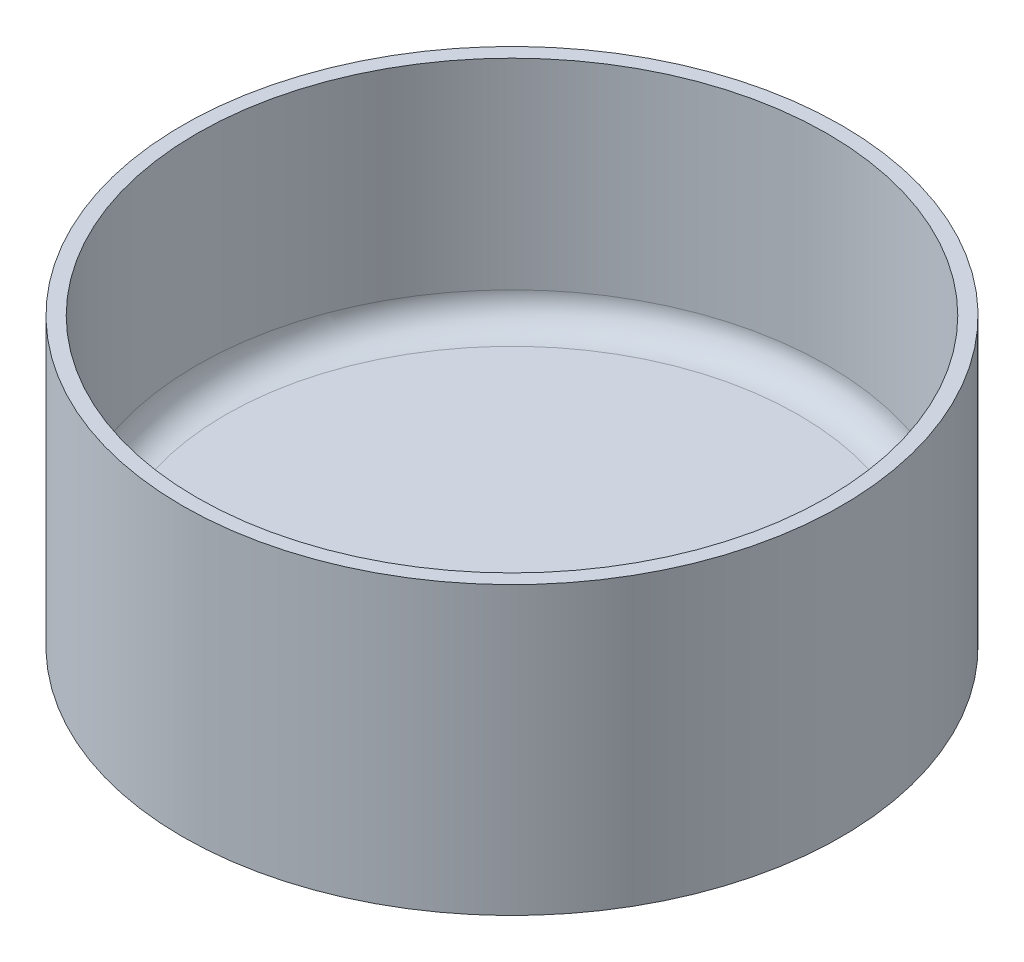
SolidWorks part; units mm, degrees
ref_plane "Front Plane" through (0, 0, 0) normal (0, 0, 1) x (1, 0, 0)
ref_plane "Top Plane" through (0, 0, 0) normal (0, 1, 0) x (1, 0, 0)
ref_plane "Right Plane" through (0, 0, 0) normal (1, 0, 0) x (0, 0, -1)
sketch "Sketch1" plane through (0, 0, 0) normal (0, 1, 0) x (1, 0, 0)
  circle A0 centre (0, 0) radius 11.5
  dimension "D1" = 23
extrude "Boss-Extrude1" add sketch "Sketch1" along normal blind 10
sketch "Sketch2" plane through (0, 10, 0) normal (0, 1, 0) x (1, 0, 0)
  circle A0 centre (0, 0) radius 11
  dimension "D1" = 22
extrude "Cut-Extrude1" cut sketch "Sketch2" against normal offset from surface (8 mm away) 2 up to face at (0, 0, 11.5)
fillet "Fillet1" radius 1 1 edges at (0, 2, 11)
